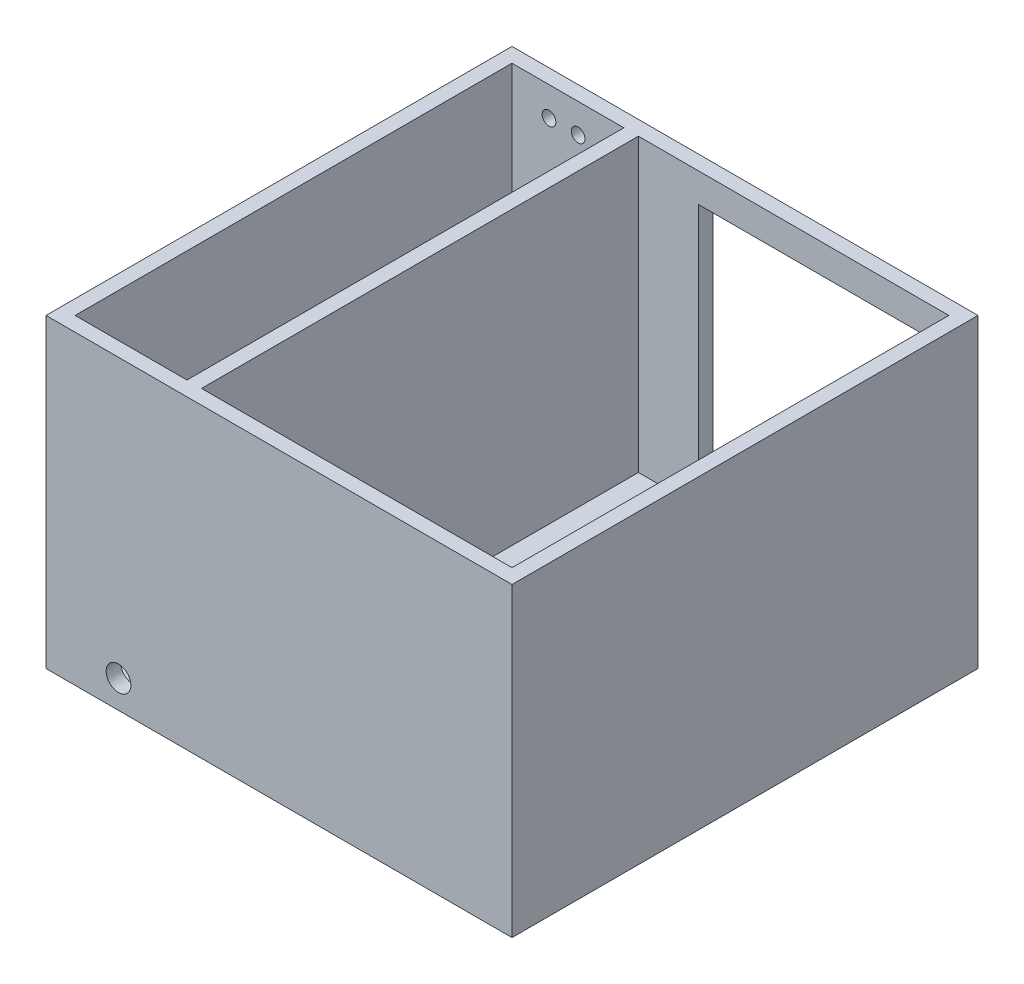
SolidWorks part; units mm, degrees
ref_plane "Front Plane" through (0, 0, 0) normal (0, 0, 1) x (1, 0, 0)
ref_plane "Top Plane" through (0, 0, 0) normal (0, 1, 0) x (1, 0, 0)
ref_plane "Right Plane" through (0, 0, 0) normal (1, 0, 0) x (0, 0, -1)
sketch "Sketch1" plane through (0, 0, 0) normal (0, 0, 1) x (1, 0, 0)
  line L1 (0, 0) -> (-203.2, 0)
  line L2 (0, 0) -> (0, 127)
  line L3 (0, 127) -> (-203.2, 127)
  line L4 (-203.2, 0) -> (-203.2, 127)
  dimension "D1" = 203.2
  dimension "D2" = 127
extrude "Boss-Extrude1" add sketch "Sketch1" along normal blind 6.35 contours L3 L4 L1 L2
sketch "Sketch2" plane through (0, 0, 6.35) normal (0, 0, 1) x (1, 0, 0)
  line L0 (-64.77, 114.3) -> (-64.77, 12.7) construction
  line L1 (-115.57, 114.3) -> (-13.97, 114.3)
  line L2 (-115.57, 114.3) -> (-115.57, 12.7)
  line L3 (-115.57, 12.7) -> (-13.97, 12.7)
  line L4 (-13.97, 114.3) -> (-13.97, 12.7)
  line L5 (-115.57, 63.5) -> (-13.97, 63.5) construction
  line L6 (-159.385, 12.7) -> (-159.385, 16.002) construction
  line L7 (-170.688, 14.351) -> (-148.082, 14.351) construction
  line L8 (0, 0) -> (-203.2, 0) construction
  line L9 (-203.2, 0) -> (-203.2, 127) construction
  line L10 (0, 0) -> (0, 127) construction
  line L16 (-170.688, 16.002) -> (-148.082, 16.002)
  line L17 (-170.688, 16.002) -> (-170.688, 12.7)
  line L18 (-170.688, 12.7) -> (-148.082, 12.7)
  line L19 (-148.082, 16.002) -> (-148.082, 12.7)
  point P20 (-159.385, 14.351)
  dimension "D1" = 101.6
  dimension "D2" = 12.7
  dimension "D3" = 101.6
  dimension "D4" = 22.606
  dimension "D5" = 3.302
  dimension "D6" = 13.97
  dimension "D7" = 43.815
  dimension "D8" = 12.7
extrude "Cut-Extrude1" cut sketch "Sketch2" against normal up to surface (6.35 mm away) up to face at (-101.6, 63.5, 0)
sketch "Sketch3" plane through (0, 0, 0) normal (0, -1, 0) x (1, 0, 0)
  line L1 (-203.2, 0) -> (0, 0)
  line L2 (-203.2, 0) -> (-203.2, 203.2)
  line L3 (-203.2, 203.2) -> (0, 203.2)
  line L4 (0, 0) -> (0, 203.2)
  dimension "D1" = 203.2
  dimension "D2" = 203.2
extrude "Boss-Extrude2" add sketch "Sketch3" along normal blind 6.35 contours L3 L4 L1 L2
sketch "Sketch4" plane through (-203.2, 0, 0) normal (-1, 0, 0) x (0, 0, 1)
  line L1 (6.35, 0) -> (203.2, 0)
  line L2 (6.35, 0) -> (6.35, 127)
  line L3 (6.35, 127) -> (203.2, 127)
  line L4 (203.2, 0) -> (203.2, 127)
extrude "Boss-Extrude3" add sketch "Sketch4" against normal blind 6.35 contours L3 L4 L1 L2
ref_plane "Plane1" through (-101.6, 0, 0) normal (1, 0, 0) x (0, 0, -1)
mirror "Mirror1" about plane through (-101.6, 0, 0) normal (1, 0, 0) of "Boss-Extrude3"
sketch "Sketch5" plane through (0, 0, 203.2) normal (0, 0, 1) x (1, 0, 0)
  line L1 (-196.85, 0) -> (-6.35, 0)
  line L2 (-196.85, 0) -> (-196.85, 127)
  line L3 (-196.85, 127) -> (-6.35, 127)
  line L4 (-6.35, 0) -> (-6.35, 127)
extrude "Boss-Extrude4" add sketch "Sketch5" against normal blind 6.35 contours L3 L4 L1 L2
sketch "Sketch7" plane through (0, 0, 0) normal (0, 1, 0) x (1, 0, 0)
  line L0 (-6.35, -6.35) -> (-196.85, -6.35) construction
  line L1 (-148.082, -6.35) -> (-141.732, -6.35)
  line L2 (-148.082, -6.35) -> (-148.082, -196.85)
  line L3 (-148.082, -196.85) -> (-141.732, -196.85)
  line L4 (-141.732, -6.35) -> (-141.732, -196.85)
  line L5 (-196.85, -196.85) -> (-6.35, -196.85) construction
  line L7 (-203.2, -203.2) -> (-203.2, 0) construction
  dimension "D1" = 55.118
  dimension "D2" = 6.35
extrude "Boss-Extrude5" add sketch "Sketch7" along normal up to surface (127 mm away) contours L4 L3 L2 L1 up to face at (-101.6, 127, 101.6)
sketch "Sketch8" plane through (0, 0, 203.2) normal (0, 0, 1) x (1, 0, 0)
  line L6 (-203.2, -6.35) -> (-203.2, 127) construction
  line L17 (-171.577, 5.7785) -> (-171.577, 0.381) construction
  line L18 (-203.2, -6.35) -> (0, -6.35) construction
  circle A0 centre (-171.577, 5.7785) radius 5.3975
  dimension "D2" = 10.795
  dimension "D3" = 6.731
  dimension "D1" = 31.623
extrude "Cut-Extrude2" cut sketch "Sketch8" against normal up to surface (6.35 mm away) up to face at (-172.466, 63.5, 196.85)
sketch "Sketch9" plane through (0, 0, 0) normal (0, 0, -1) x (-1, 0, 0)
  line L0 (168.021, 114.3) -> (180.721, 114.3) construction
  line L2 (115.2594, 114.3) -> (165.0238, 114.3) construction
  line L3 (13.97, 114.3) -> (115.57, 114.3) construction
  circle A0 centre (168.021, 114.3) radius 2.9972
  circle A1 centre (180.721, 114.3) radius 2.9972
  point P4 (174.371, 114.3)
  dimension "D1" = 5.9944
  dimension "D2" = 5.9944
  dimension "D3" = 12.7
  dimension "D4" = 26.289
extrude "Cut-Extrude3" cut sketch "Sketch9" against normal up to surface (6.35 mm away) up to face at (-165.9255, 38.9255, 6.35)
